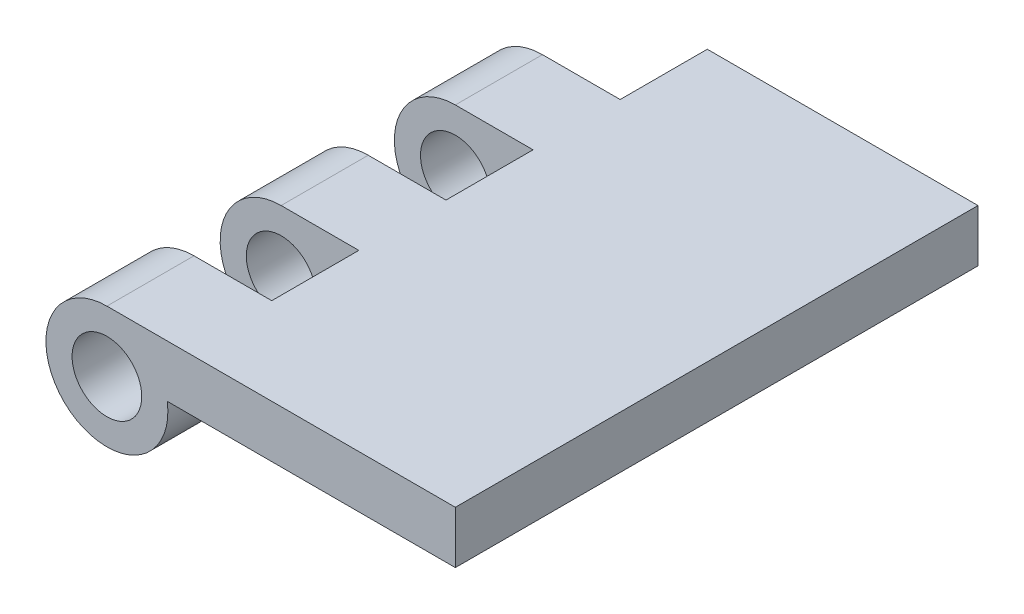
SolidWorks part; units mm, degrees
ref_plane "前视基准面" through (0, 0, 0) normal (0, 0, 1) x (1, 0, 0)
ref_plane "上视基准面" through (0, 0, 0) normal (0, 1, 0) x (1, 0, 0)
ref_plane "右视基准面" through (0, 0, 0) normal (1, 0, 0) x (0, 0, -1)
other "Configuration Table"
sketch "草图1" plane through (0, 0, 0) normal (0, 0, 1) x (1, 0, 0)
  line L0 (0, -3.5) -> (20, -3.5)
  line L1 (20, -3.5) -> (20, -0.5)
  line L2 (20, -0.5) -> (3.4641, -0.5)
  arc A0 (3.4641, -0.5) -> (0, -3.5) centre (0, 0) ccw
  circle A1 centre (0, 0) radius 2
  dimension "D1" = 4
  dimension "D2" = 7
  dimension "D3" = 20
  dimension "D4" = 3
  dimension "D5" = 1.5
sketch "草图2" plane through (0, 0, 0) normal (0, 0, 1) x (1, 0, 0)
extrude "凸台-拉伸1" add sketch "草图1" along normal mid plane 30
sketch "草图3" plane through (0, 0, 0) normal (0, 1, 0) x (1, 0, 0)
  line L1 (-6.7865, 10) -> (4.4606, 10)
  line L2 (-6.7865, 10) -> (-6.7865, 5)
  line L3 (-6.7865, 5) -> (4.4606, 5)
  line L4 (4.4606, 10) -> (4.4606, 5)
  line L5 (-6.7865, 0) -> (4.4606, 0)
  line L6 (-6.7865, 0) -> (-6.7865, -5)
  line L7 (-6.7865, -5) -> (4.4606, -5)
  line L8 (4.4606, 0) -> (4.4606, -5)
  line L9 (3.5, 15) -> (-3.5, 15) construction
  line L10 (-8.5603, -10) -> (4.4606, -10)
  line L11 (-8.5603, -10) -> (-8.5603, -17.8609)
  line L12 (-8.5603, -17.8609) -> (4.4606, -17.8609)
  line L13 (4.4606, -10) -> (4.4606, -17.8609)
  dimension "D1" = 5
  dimension "D2" = 5
  dimension "D3" = 5
  dimension "D4" = 5
  dimension "D5" = 5
extrude "切除-拉伸1" cut sketch "草图3" against normal mid plane 30 contours L11 L12 L13 L10 | L5 L8 L7 L6 | L2 L3 L4 L1
mirror "镜向1" about plane through (0, 0, -15) normal (0, 0, 1) of bodies 107
mirror "镜向2" about plane through (0, -3.5, -45) normal (0, 1, 0) of bodies 108
delete or keep bodies "实体-删除/保留 1" type delete bodies bodies 108 107
